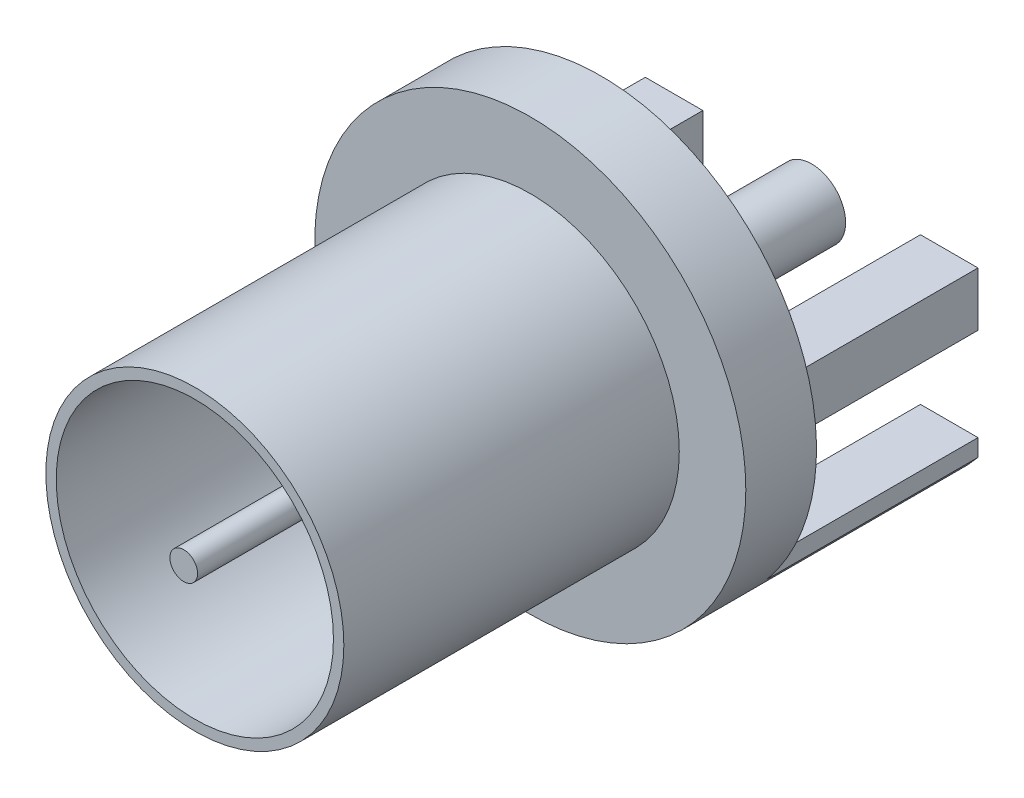
SolidWorks part; units mm, degrees
material "6061 Alloy"
ref_plane "Front Plane" through (0, 0, 0) normal (0, 0, 1) x (1, 0, 0)
ref_plane "Top Plane" through (0, 0, 0) normal (0, 1, 0) x (1, 0, 0)
ref_plane "Right Plane" through (0, 0, 0) normal (1, 0, 0) x (0, 0, -1)
sketch "Sketch1" plane through (0, 0, 0) normal (0, 0, 1) x (1, 0, 0)
  circle A0 centre (0, 0) radius 3.9497
  dimension "D1" = 7.8994
extrude "Boss-Extrude1" add sketch "Sketch1" along normal blind 1.2954
sketch "Sketch2" plane through (0, 0, 1.2954) normal (0, 0, 1) x (1, 0, 0)
  circle A0 centre (0, 0) radius 2.7305
  circle A1 centre (0, 0) radius 2.54
  dimension "D1" = 5.461
  dimension "D2" = 5.08
extrude "Boss-Extrude2" add sketch "Sketch2" along normal blind 6.1468
sketch "Sketch3" plane through (0, 0, 0) normal (0, 0, -1) x (-1, 0, 0)
  line L0 (1.9939, 0.4729) -> (3.048, 0.4729)
  line L1 (-3.048, 0.4953) -> (-1.9939, 0.4953)
  line L2 (-3.048, 0.4953) -> (-3.048, -0.4953)
  line L3 (-3.048, -0.4953) -> (-1.9939, -0.4953)
  line L4 (-1.9939, 0.4953) -> (-1.9939, -0.4953)
  line L5 (1.9939, 0.4729) -> (1.9939, -0.4953)
  line L6 (1.9939, -0.4953) -> (3.048, -0.4953)
  line L7 (3.048, 0.4729) -> (3.048, -0.4953)
  line L8 (-1.9939, -3.4095) -> (-1.9939, -2.1971)
  line L9 (-1.9939, -2.1971) -> (-3.048, -2.1971)
  line L10 (-3.048, -2.1971) -> (-3.048, -2.5119)
  line L11 (1.9939, -2.1971) -> (3.048, -2.1971)
  line L12 (3.048, -2.1971) -> (3.048, -2.5119)
  line L13 (1.9939, -2.1971) -> (1.9939, -3.4095)
  circle A0 centre (0, 0) radius 3.9497 construction
  arc A1 (-3.048, -2.5119) -> (-1.9939, -3.4095) centre (0, 0) ccw
  arc A2 (1.9939, -3.4095) -> (3.048, -2.5119) centre (0, 0) ccw
  dimension "D1" = 0.9906
  dimension "D2" = 1.0541
  dimension "D3" = 1.9939
  dimension "D4" = 0.4953
  dimension "D5" = 1.9939
  dimension "D6" = 0.4953
  dimension "D7" = 1.7018
extrude "Boss-Extrude3" add sketch "Sketch3" along normal blind 3.8608
sketch "Sketch4" plane through (0, 0, 0) normal (0, 0, -1) x (-1, 0, 0)
  circle A0 centre (0, 0) radius 0.6223
  dimension "D1" = 1.2446
extrude "Boss-Extrude4" add sketch "Sketch4" along normal blind 3.8608
sketch "Sketch5" plane through (0, 0, 1.2954) normal (0, 0, 1) x (1, 0, 0)
  circle A0 centre (0, 0) radius 0.254
extrude "Boss-Extrude5" add sketch "Sketch5" along normal blind 6.35
sketch "Sketch8" plane through (0, 0, 1.2954) normal (0, 0, 1) x (1, 0, 0)
  circle A0 centre (0, 0) radius 3.2258 construction
  dimension "D1" = 6.4516
